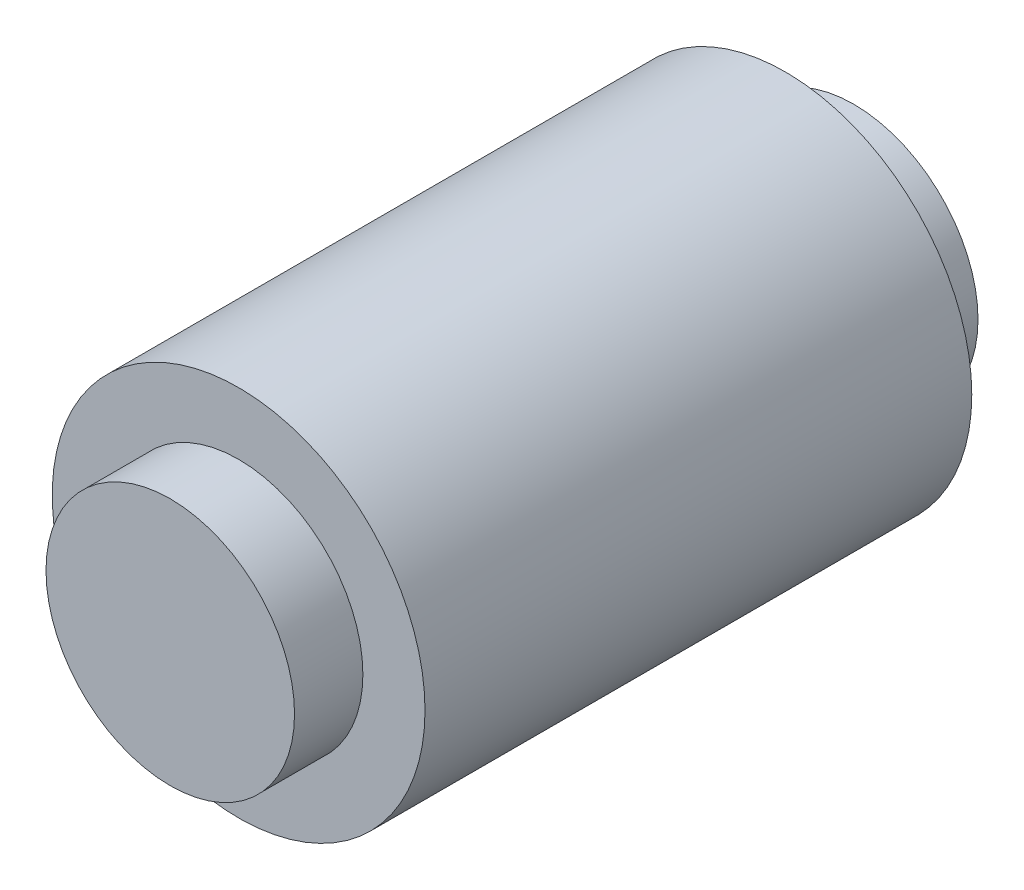
SolidWorks part; units mm, degrees
ref_plane "Front Plane" through (0, 0, 0) normal (0, 0, 1) x (1, 0, 0)
ref_plane "Top Plane" through (0, 0, 0) normal (0, 1, 0) x (1, 0, 0)
ref_plane "Right Plane" through (0, 0, 0) normal (1, 0, 0) x (0, 0, -1)
sketch "Sketch1" plane through (0, 0, 0) normal (0, 0, 1) x (1, 0, 0)
  circle A0 centre (0, 0) radius 15
  dimension "D1" = 30
extrude "Boss-Extrude1" add sketch "Sketch1" along normal blind 44
sketch "Sketch4" plane through (0, 0, 44) normal (0, 0, 1) x (1, 0, 0)
  circle A0 centre (0, 0) radius 10
  dimension "D1" = 20
extrude "Boss-Extrude2" add sketch "Sketch4" along normal blind 5.5 contours A0
sketch "Sketch5" plane through (0, 0, 0) normal (0, 0, -1) x (-1, 0, 0)
  circle A0 centre (0, 0) radius 10
  dimension "D1" = 20
extrude "Boss-Extrude3" add sketch "Sketch5" along normal blind 5.5
